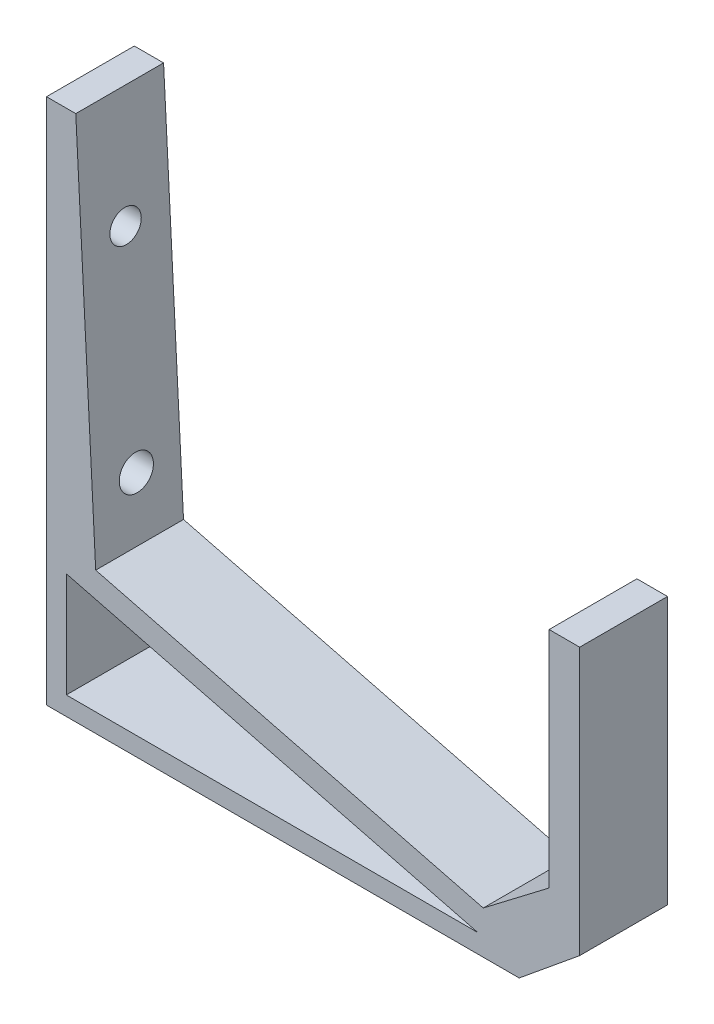
SolidWorks part; units mm, degrees
ref_plane "Front Plane" through (0, 0, 0) normal (0, 0, 1) x (1, 0, 0)
ref_plane "Top Plane" through (0, 0, 0) normal (0, 1, 0) x (1, 0, 0)
ref_plane "Right Plane" through (0, 0, 0) normal (1, 0, 0) x (0, 0, -1)
sketch "Esquisse1" plane through (0, 0, 0) normal (0, 0, 1) x (1, 0, 0)
  line L0 (-14.0502, 18.4484) -> (-4.0502, 18.4484)
  line L1 (-4.0502, 18.4484) -> (2.7618, -113.2229)
  line L2 (2.7618, -113.2229) -> (135.1504, -146.9825)
  line L3 (135.1504, -146.9825) -> (157.6594, -129.8043)
  line L4 (157.6594, -129.8043) -> (157.6594, -53.3331)
  line L5 (157.6594, -53.3331) -> (168.1064, -53.3331)
  line L6 (168.1064, -144.596) -> (147.4315, -161.5516)
  line L7 (147.4315, -161.5516) -> (-14.0502, -161.5516)
  line L8 (-14.0502, -161.5516) -> (-14.0502, 18.4484)
  line L9 (168.1064, -53.3331) -> (168.1064, -144.596)
  point P7 (7.9452, -115.2504)
  point P10 (-4.0502, -111.7423)
  point P11 (2.7618, -113.2229)
  point P12 (0, 0)
  point P13 (135.1504, -146.9825)
  point P14 (0, 0)
  point P15 (157.6594, -129.8043)
  dimension "D1" = 10
  dimension "D2" = 180
extrude "Boss.-Extru.1" add sketch "Esquisse1" along normal blind 30
sketch "Esquisse3" plane through (-14.0502, 0, 0) normal (-1, 0, 0) x (0, 0, 1)
  circle A0 centre (15.0372, -92.3376) radius 5.8328
  circle A1 centre (15.0372, -21.2644) radius 5.3513
extrude "Enlèv. mat.-Extru.1" cut sketch "Esquisse3" against normal up to next
sketch "Esquisse4" plane through (-14.0502, 0, 0) normal (-1, 0, 0) x (0, 0, 1)
  line L0 (0.0745, -92.3376) -> (30, -92.3376)
  line L1 (30, 18.4484) -> (30, -161.5516) construction
  point P6 (15.0372, -92.3376)
sketch "Esquisse5" plane through (0, 0, 30) normal (0, 0, 1) x (1, 0, 0)
  line L0 (-7.2867, -119.3046) -> (133.3364, -155.1639)
  line L1 (133.3364, -155.1639) -> (-7.2867, -155.1639)
  line L2 (-7.2867, -155.1639) -> (-7.2867, -119.3046)
  line L3 (135.1504, -146.9825) -> (2.7618, -113.2229) construction
extrude "Enlèv. mat.-Extru.2" cut sketch "Esquisse5" against normal through all
